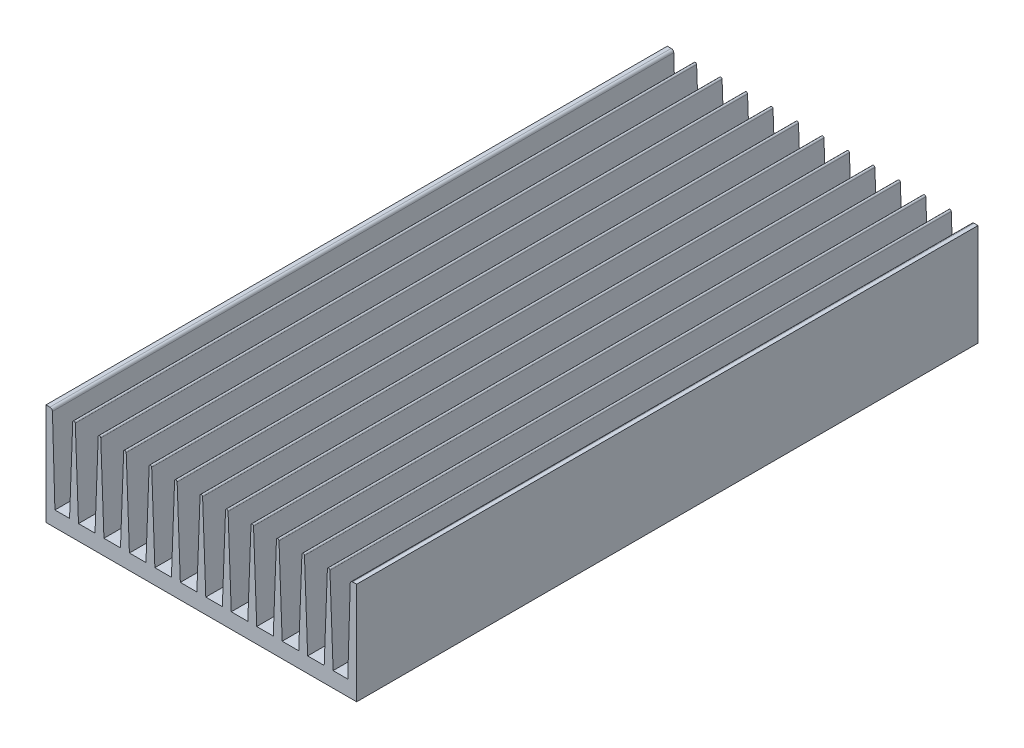
SolidWorks part; units mm, degrees
ref_plane "Спереди" through (0, 0, 0) normal (0, 0, 1) x (1, 0, 0)
ref_plane "Сверху" through (0, 0, 0) normal (0, 1, 0) x (1, 0, 0)
ref_plane "Справа" through (0, 0, 0) normal (1, 0, 0) x (0, 0, -1)
sketch "Эскиз1" plane through (0, 0, 0) normal (0, 0, 1) x (1, 0, 0)
  line L0 (0, 40) -> (1.529, 40)
  line L1 (0, 0) -> (122, 0)
  line L2 (2.5285, 39.0294) -> (3.5, 6)
  line L3 (0, 40) -> (0, 0)
  line L4 (122, 40) -> (122, 0)
  line L5 (61, 63.7127) -> (61, -22.2582) construction
  line L8 (122, 40) -> (120.471, 40)
  line L9 (119.4715, 39.0294) -> (118.5, 6)
  line L10 (3.5, 6) -> (118.5, 6)
  arc A0 (1.529, 40) -> (2.5285, 39.0294) centre (1.529, 39) cw
  arc A2 (120.471, 40) -> (119.4715, 39.0294) centre (120.471, 39) ccw
  point P18 (119.5, 40)
  dimension "D9" = 1
  dimension "D1" = 122
  dimension "D2" = 6
  dimension "D3" = 40
  dimension "D4" = 3.5
  dimension "D7" = 2.5
extrude "Вытянуть1" add sketch "Эскиз1" along normal blind 244
sketch "Эскиз2" plane through (0, 0, 244) normal (0, 0, 1) x (1, 0, 0)
  line L0 (118.5, 6) -> (3.5, 6) construction
  line L1 (10.5, 39.5) -> (9.25, 6)
  line L2 (11, 39.5) -> (11, 22.5548) construction
  line L3 (11.5, 39.5) -> (12.75, 6)
  line L4 (9.25, 6) -> (12.75, 6)
  line L6 (0, 40) -> (0, 0) construction
  arc A0 (10.5, 39.5) -> (11.5, 39.5) centre (11, 39.5) cw
  dimension "D1" = 34
  dimension "D3" = 0.5
  dimension "D2" = 3.5
  dimension "D4" = 11
  dimension "D5" = 1
extrude "Вытянуть3" add sketch "Эскиз2" against normal blind 244
pattern_curve "Кривая1" of "Вытянуть3" along edge at (61, 0, 0) parameters "D1"=11, "D3"=10, "D2"=1, "D4"=50
sketch "Эскиз3" plane through (0, 0, 0) normal (0, -1, 0) x (1, 0, 0)
  line L0 (-14.0506, 236) -> (137.5079, 236) construction
  line L1 (0, 244) -> (122, 244) construction
  line L2 (0, 244) -> (0, 0) construction
  line L3 (-46.7511, 122) -> (151.4312, 122) construction
  line L4 (0, 0) -> (122, 0) construction
  circle A0 centre (26, 236) radius 2.25
  circle A1 centre (96, 236) radius 2.25
  circle A2 centre (96, 8) radius 2.25
  circle A3 centre (26, 8) radius 2.25
  dimension "D2" = 70
  dimension "D4" = 4.5
  dimension "D1" = 8
  dimension "D3" = 26
extrude "Вырез-Вытянуть1" cut sketch "Эскиз3" against normal blind 6
sketch "Эскиз4" plane through (-5.7236, 0, -26.359) normal (0, -1, 0) x (1, 0, 0)
  line L0 (55.7236, 158.359) -> (55.7236, 64.1478) construction
  line L1 (55.7236, 173.359) -> (55.7236, 49.359) construction
  line L2 (5.7236, 26.359) -> (127.7236, 26.359) construction
  line L3 (55.7236, 173.359) -> (55.7236, 134.359) construction
  line L5 (127.7236, 270.359) -> (127.7236, 26.359) construction
  line L7 (55.7236, 134.359) -> (73.7236, 134.359) construction
  line L8 (73.7236, 134.359) -> (73.7236, 86.359) construction
  circle A1 centre (55.7236, 158.359) radius 1.6
  circle A2 centre (55.7236, 53.359) radius 1.6
  circle A3 centre (55.7236, 173.359) radius 1.6
  circle A4 centre (73.7236, 86.359) radius 1.6
  circle A6 centre (73.7236, 134.359) radius 1.6
  circle A7 centre (84.7236, 110.359) radius 2.6
  circle A8 centre (17.7236, 220.359) radius 2.1
  dimension "D6" = 147
  dimension "D9" = 27
  dimension "D12" = 3.2
  dimension "D14" = 54
  dimension "D5" = 108
  dimension "D13" = 60
  dimension "D15" = 5.2
  dimension "D16" = 43
  dimension "D17" = 84
  dimension "D20" = 4.2
  dimension "D1" = 105
  dimension "D8" = 72
  dimension "D11" = 72
  dimension "D18" = 110
  dimension "D19" = 194
extrude "Вырез-Вытянуть2" cut sketch "Эскиз4" against normal blind 5.5
cosmetic thread "Условное изображение резьбы11" parameters "D2"=4
cosmetic thread "Условное изображение резьбы12" parameters "D2"=4
cosmetic thread "Условное изображение резьбы14" parameters "D2"=4
cosmetic thread "Условное изображение резьбы15" parameters "D2"=4
cosmetic thread "Условное изображение резьбы16" parameters "D2"=4
cosmetic thread "Условное изображение резьбы17" parameters "D2"=6
cosmetic thread "Условное изображение резьбы18" parameters "D2"=5
